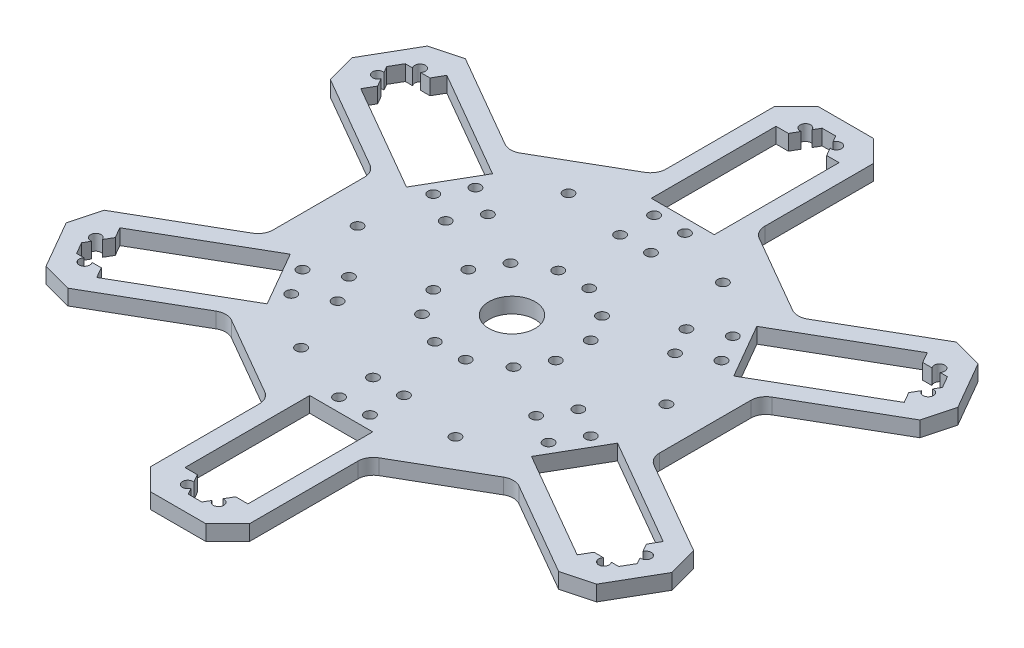
SolidWorks part; units mm, degrees
ref_plane "前视基准面" through (0, 0, 0) normal (0, 0, 1) x (1, 0, 0)
ref_plane "上视基准面" through (0, 0, 0) normal (0, 1, 0) x (1, 0, 0)
ref_plane "右视基准面" through (0, 0, 0) normal (1, 0, 0) x (0, 0, -1)
sketch "草图1" plane through (0, 0, 0) normal (0, 1, 0) x (1, 0, 0)
  line L0 (1497.2797, 1171.1891) -> (1471.7201, 1185.946)
  line L1 (1438.0011, 1289.4292) -> (1472.9885, 1269.2292)
  line L2 (1472.9885, 1269.2292) -> (1462.7885, 1251.5623)
  line L3 (1462.7885, 1251.5623) -> (1427.8011, 1271.7623)
  line L4 (1427.8011, 1193.7292) -> (1462.7885, 1213.9292)
  line L5 (1462.7885, 1213.9292) -> (1472.9885, 1196.2623)
  line L6 (1472.9885, 1196.2623) -> (1438.0011, 1176.0623)
  line L7 (1505.5797, 1137.0458) -> (1505.5797, 1177.4458)
  line L8 (1505.5797, 1177.4458) -> (1525.9797, 1177.4458)
  line L9 (1525.9797, 1177.4458) -> (1525.9797, 1137.0458)
  line L10 (1593.5583, 1176.0623) -> (1558.5709, 1196.2623)
  line L11 (1558.5709, 1196.2623) -> (1568.7709, 1213.9292)
  line L12 (1568.7709, 1213.9292) -> (1603.7583, 1193.7292)
  line L13 (1603.7583, 1271.7623) -> (1568.7709, 1251.5623)
  line L14 (1568.7709, 1251.5623) -> (1558.5709, 1269.2292)
  line L15 (1558.5709, 1269.2292) -> (1593.5583, 1289.4292)
  line L16 (1525.9797, 1288.0458) -> (1505.5797, 1288.0458)
  line L17 (1505.5797, 1288.0458) -> (1505.5797, 1328.4458)
  line L18 (1499.7797, 1166.859) -> (1499.7797, 1131.7458)
  line L19 (1531.7797, 1166.859) -> (1531.7797, 1131.7458)
  line L20 (1559.8393, 1185.946) -> (1534.2797, 1171.1891)
  line L21 (1564.8393, 1185.946) -> (1595.2482, 1168.3894)
  line L22 (1580.8393, 1213.6588) -> (1611.2482, 1196.1022)
  line L23 (1578.3393, 1247.5026) -> (1578.3393, 1217.9889)
  line L24 (1580.8393, 1251.8327) -> (1611.2482, 1269.3894)
  line L25 (1564.8393, 1279.5456) -> (1595.2482, 1297.1022)
  line L26 (1534.2797, 1294.3024) -> (1559.8393, 1279.5456)
  line L27 (1531.7797, 1298.6325) -> (1531.7797, 1333.7458)
  line L28 (1499.7797, 1298.6325) -> (1499.7797, 1333.7458)
  line L29 (1471.7201, 1279.5456) -> (1497.2797, 1294.3024)
  line L30 (1466.7201, 1279.5456) -> (1436.3111, 1297.1022)
  line L31 (1450.7201, 1251.8327) -> (1420.3111, 1269.3894)
  line L32 (1453.2201, 1217.9889) -> (1453.2201, 1247.5026)
  line L33 (1450.7201, 1213.6588) -> (1420.3111, 1196.1022)
  line L34 (1466.7201, 1185.946) -> (1436.3111, 1168.3894)
  line L35 (1525.9797, 1288.0458) -> (1525.9797, 1328.4458)
  line L36 (1505.5797, 1328.4458) -> (1509.5797, 1328.4458)
  line L37 (1509.5797, 1328.4458) -> (1511.0982, 1331.0759)
  line L38 (1525.9797, 1328.4458) -> (1521.9797, 1328.4458)
  line L39 (1521.9797, 1328.4458) -> (1520.4612, 1331.0759)
  line L40 (1517.9797, 1335.374) -> (1513.5797, 1335.374)
  line L41 (1512.3851, 1333.3049) -> (1513.5797, 1335.374)
  line L42 (1519.1743, 1333.3049) -> (1517.9797, 1335.374)
  line L43 (1427.8011, 1271.7623) -> (1429.8011, 1275.2264)
  line L44 (1429.8011, 1275.2264) -> (1428.2826, 1277.8565)
  line L45 (1426.9956, 1280.0855) -> (1425.8011, 1282.1546)
  line L46 (1438.0011, 1289.4292) -> (1436.0011, 1285.9651)
  line L47 (1436.0011, 1285.9651) -> (1432.9641, 1285.9651)
  line L48 (1430.3902, 1285.9651) -> (1428.0011, 1285.9651)
  line L49 (1428.0011, 1285.9651) -> (1425.8011, 1282.1546)
  line L50 (1438.0011, 1176.0623) -> (1436.0011, 1179.5264)
  line L51 (1436.0011, 1179.5264) -> (1432.9641, 1179.5264)
  line L52 (1430.3902, 1179.5264) -> (1428.0011, 1179.5264)
  line L53 (1427.8011, 1193.7292) -> (1429.8011, 1190.2651)
  line L54 (1429.8011, 1190.2651) -> (1428.2826, 1187.635)
  line L55 (1426.9956, 1185.406) -> (1425.8011, 1183.3369)
  line L56 (1425.8011, 1183.3369) -> (1428.0011, 1179.5264)
  line L57 (1525.9797, 1137.0458) -> (1521.9797, 1137.0458)
  line L58 (1521.9797, 1137.0458) -> (1520.4612, 1134.4157)
  line L59 (1519.1743, 1132.1866) -> (1517.9797, 1130.1176)
  line L60 (1505.5797, 1137.0458) -> (1509.5797, 1137.0458)
  line L61 (1509.5797, 1137.0458) -> (1511.0982, 1134.4157)
  line L62 (1512.3851, 1132.1866) -> (1513.5797, 1130.1176)
  line L63 (1513.5797, 1130.1176) -> (1517.9797, 1130.1176)
  line L64 (1603.7583, 1193.7292) -> (1601.7583, 1190.2651)
  line L65 (1601.7583, 1190.2651) -> (1603.2768, 1187.635)
  line L66 (1604.5637, 1185.406) -> (1605.7583, 1183.3369)
  line L67 (1593.5583, 1176.0623) -> (1595.5583, 1179.5264)
  line L68 (1595.5583, 1179.5264) -> (1598.5953, 1179.5264)
  line L69 (1601.1692, 1179.5264) -> (1603.5583, 1179.5264)
  line L70 (1603.5583, 1179.5264) -> (1605.7583, 1183.3369)
  line L71 (1593.5583, 1289.4292) -> (1595.5583, 1285.9651)
  line L72 (1595.5583, 1285.9651) -> (1598.5953, 1285.9651)
  line L73 (1601.1692, 1285.9651) -> (1603.5583, 1285.9651)
  line L74 (1603.7583, 1271.7623) -> (1601.7583, 1275.2264)
  line L75 (1601.7583, 1275.2264) -> (1603.2768, 1277.8565)
  line L76 (1604.5637, 1280.0855) -> (1605.7583, 1282.1546)
  line L77 (1605.7583, 1282.1546) -> (1603.5583, 1285.9651)
  line L78 (1499.7797, 1333.7458) -> (1506.8507, 1340.8168)
  line L79 (1531.7797, 1333.7458) -> (1524.7086, 1340.8168)
  line L80 (1524.7086, 1340.8168) -> (1506.8507, 1340.8168)
  line L81 (1420.3111, 1269.3894) -> (1417.7229, 1279.0486)
  line L82 (1436.3111, 1297.1022) -> (1426.6519, 1294.514)
  line L83 (1426.6519, 1294.514) -> (1417.7229, 1279.0486)
  line L84 (1436.3111, 1168.3894) -> (1426.6519, 1170.9776)
  line L85 (1420.3111, 1196.1022) -> (1417.7229, 1186.4429)
  line L86 (1417.7229, 1186.4429) -> (1426.6519, 1170.9776)
  line L87 (1531.7797, 1131.7458) -> (1524.7086, 1124.6747)
  line L88 (1499.7797, 1131.7458) -> (1506.8507, 1124.6747)
  line L89 (1506.8507, 1124.6747) -> (1524.7086, 1124.6747)
  line L90 (1611.2482, 1196.1022) -> (1613.8364, 1186.4429)
  line L91 (1595.2482, 1168.3894) -> (1604.9075, 1170.9776)
  line L92 (1604.9075, 1170.9776) -> (1613.8364, 1186.4429)
  line L93 (1595.2482, 1297.1022) -> (1604.9075, 1294.514)
  line L94 (1611.2482, 1269.3894) -> (1613.8364, 1279.0486)
  line L95 (1613.8364, 1279.0486) -> (1604.9075, 1294.514)
  circle A0 centre (1474.1124, 1262.5759) radius 1.7
  circle A1 centre (1469.1124, 1253.9156) radius 1.7
  circle A2 centre (1483.6387, 1257.0759) radius 1.7
  circle A3 centre (1478.6387, 1248.4156) radius 1.7
  circle A4 centre (1500.9592, 1247.0759) radius 1.7
  circle A5 centre (1495.9592, 1238.4156) radius 1.7
  circle A6 centre (1465.7797, 1232.7458) radius 1.7
  circle A7 centre (1469.1124, 1211.5759) radius 1.7
  circle A8 centre (1474.1124, 1202.9156) radius 1.7
  circle A9 centre (1478.6387, 1217.0759) radius 1.7
  circle A10 centre (1483.6387, 1208.4156) radius 1.7
  circle A11 centre (1495.9592, 1227.0759) radius 1.7
  circle A12 centre (1500.9592, 1218.4156) radius 1.7
  circle A13 centre (1490.7797, 1189.4445) radius 1.7
  circle A14 centre (1510.7797, 1181.7458) radius 1.7
  circle A15 centre (1520.7797, 1181.7458) radius 1.7
  circle A16 centre (1510.7797, 1192.7458) radius 1.7
  circle A17 centre (1520.7797, 1192.7458) radius 1.7
  circle A18 centre (1510.7797, 1212.7458) radius 1.7
  circle A19 centre (1520.7797, 1212.7458) radius 1.7
  circle A20 centre (1540.7797, 1189.4445) radius 1.7
  circle A21 centre (1557.447, 1202.9156) radius 1.7
  circle A22 centre (1562.447, 1211.5759) radius 1.7
  circle A23 centre (1547.9207, 1208.4156) radius 1.7
  circle A24 centre (1552.9207, 1217.0759) radius 1.7
  circle A25 centre (1530.6002, 1218.4156) radius 1.7
  circle A26 centre (1535.6002, 1227.0759) radius 1.7
  circle A27 centre (1565.7797, 1232.7458) radius 1.7
  circle A28 centre (1562.447, 1253.9156) radius 1.7
  circle A29 centre (1557.447, 1262.5759) radius 1.7
  circle A30 centre (1552.9207, 1248.4156) radius 1.7
  circle A31 centre (1547.9207, 1257.0759) radius 1.7
  circle A32 centre (1535.6002, 1238.4156) radius 1.7
  circle A33 centre (1530.6002, 1247.0759) radius 1.7
  circle A34 centre (1540.7797, 1276.047) radius 1.7
  arc A35 (1520.4612, 1331.0759) -> (1519.1743, 1333.3049) centre (1520.7797, 1332.7458) ccw
  arc A36 (1512.3851, 1333.3049) -> (1511.0982, 1331.0759) centre (1510.7797, 1332.7458) ccw
  circle A37 centre (1520.7797, 1283.7458) radius 1.7
  circle A38 centre (1510.7797, 1283.7458) radius 1.7
  circle A39 centre (1520.7797, 1272.7458) radius 1.7
  circle A40 centre (1510.7797, 1272.7458) radius 1.7
  circle A41 centre (1520.7797, 1252.7458) radius 1.7
  circle A42 centre (1510.7797, 1252.7458) radius 1.7
  circle A43 centre (1490.7797, 1276.047) radius 1.7
  circle A44 centre (1515.7797, 1232.7458) radius 7.5
  arc A45 (1471.7201, 1185.946) -> (1466.7201, 1185.946) centre (1469.2201, 1181.6159) ccw
  arc A46 (1450.7201, 1213.6588) -> (1453.2201, 1217.9889) centre (1448.2201, 1217.9889) ccw
  arc A47 (1453.2201, 1247.5026) -> (1450.7201, 1251.8327) centre (1448.2201, 1247.5026) ccw
  arc A48 (1466.7201, 1279.5456) -> (1471.7201, 1279.5456) centre (1469.2201, 1283.8757) ccw
  arc A49 (1497.2797, 1294.3024) -> (1499.7797, 1298.6325) centre (1494.7797, 1298.6325) ccw
  arc A50 (1531.7797, 1298.6325) -> (1534.2797, 1294.3024) centre (1536.7797, 1298.6325) ccw
  arc A51 (1559.8393, 1279.5456) -> (1564.8393, 1279.5456) centre (1562.3393, 1283.8757) ccw
  arc A52 (1580.8393, 1251.8327) -> (1578.3393, 1247.5026) centre (1583.3393, 1247.5026) ccw
  arc A53 (1578.3393, 1217.9889) -> (1580.8393, 1213.6588) centre (1583.3393, 1217.9889) ccw
  arc A54 (1564.8393, 1185.946) -> (1559.8393, 1185.946) centre (1562.3393, 1181.6159) ccw
  arc A55 (1534.2797, 1171.1891) -> (1531.7797, 1166.859) centre (1536.7797, 1166.859) ccw
  arc A56 (1499.7797, 1166.859) -> (1497.2797, 1171.1891) centre (1494.7797, 1166.859) ccw
  arc A57 (1432.9641, 1285.9651) -> (1430.3902, 1285.9651) centre (1431.6771, 1287.0759) ccw
  arc A58 (1426.9956, 1280.0855) -> (1428.2826, 1277.8565) centre (1426.6771, 1278.4156) ccw
  arc A59 (1428.2826, 1187.635) -> (1426.9956, 1185.406) centre (1426.6771, 1187.0759) ccw
  arc A60 (1430.3902, 1179.5264) -> (1432.9641, 1179.5264) centre (1431.6771, 1178.4156) ccw
  arc A61 (1511.0982, 1134.4157) -> (1512.3851, 1132.1866) centre (1510.7797, 1132.7458) ccw
  arc A62 (1519.1743, 1132.1866) -> (1520.4612, 1134.4157) centre (1520.7797, 1132.7458) ccw
  arc A63 (1598.5953, 1179.5264) -> (1601.1692, 1179.5264) centre (1599.8822, 1178.4156) ccw
  arc A64 (1604.5637, 1185.406) -> (1603.2768, 1187.635) centre (1604.8822, 1187.0759) ccw
  arc A65 (1603.2768, 1277.8565) -> (1604.5637, 1280.0855) centre (1604.8822, 1278.4156) ccw
  arc A66 (1601.1692, 1285.9651) -> (1598.5953, 1285.9651) centre (1599.8822, 1287.0759) ccw
extrude "凸台-拉伸1" add sketch "草图1" along normal blind 5
